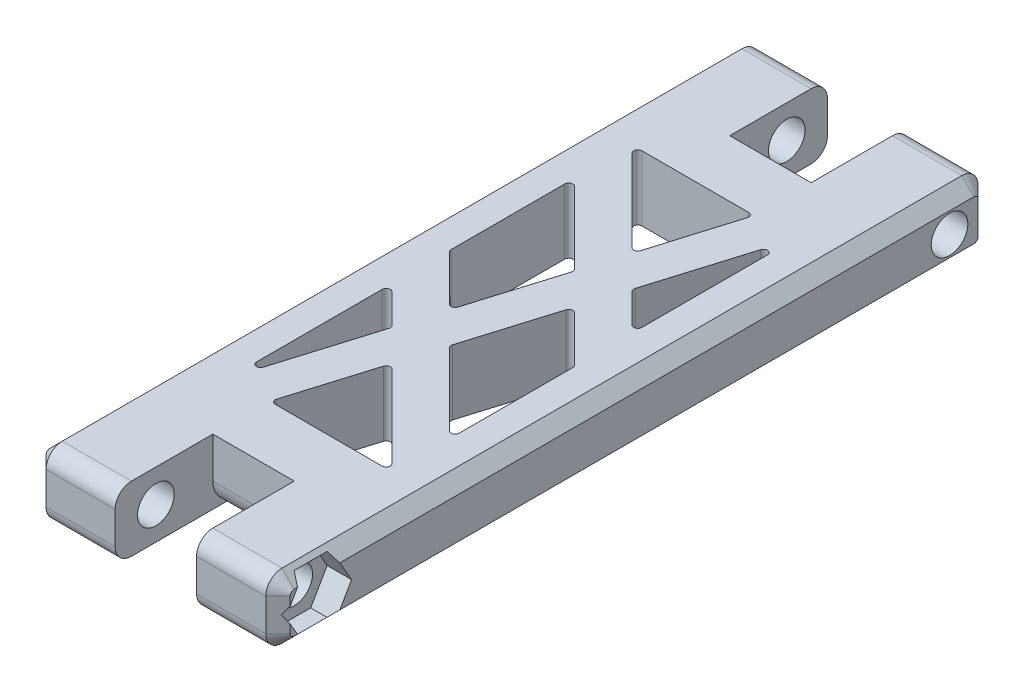
SolidWorks part; units mm, degrees
ref_plane "Front Plane" through (0, 0, 0) normal (0, 0, 1) x (1, 0, 0)
ref_plane "Top Plane" through (0, 0, 0) normal (0, 1, 0) x (1, 0, 0)
ref_plane "Right Plane" through (0, 0, 0) normal (1, 0, 0) x (0, 0, -1)
sketch "Sketch1" plane through (0, 0, 0) normal (0, 1, 0) x (1, 0, 0)
  line L1 (-15, 43.75) -> (15, 43.75)
  line L2 (-15, 43.75) -> (-15, -43.75)
  line L3 (-15, -43.75) -> (15, -43.75)
  line L4 (15, 43.75) -> (15, -43.75)
  line L5 (-15, 43.75) -> (15, -43.75) construction
  line L6 (-15, -43.75) -> (15, 43.75) construction
  point P0 (0, 0)
  dimension "D1" = 30
  dimension "D2" = 87.5
extrude "Boss-Extrude1" add sketch "Sketch1" along normal blind 8
sketch "Sketch2" plane through (0, 8, 0) normal (0, 1, 0) x (1, 0, 0)
  line L0 (15, 43.75) -> (-15, 43.75) construction
  line L1 (-5, 43.75) -> (5, 43.75)
  line L2 (-5, 43.75) -> (-5, 31.75)
  line L3 (-5, 31.75) -> (5, 31.75)
  line L4 (5, 43.75) -> (5, 31.75)
  line L5 (-15, -43.75) -> (15, -43.75) construction
  line L6 (5, -43.75) -> (-5, -43.75)
  line L7 (5, -43.75) -> (5, -31.75)
  line L8 (5, -31.75) -> (-5, -31.75)
  line L9 (-5, -43.75) -> (-5, -31.75)
  line L10 (15, -43.75) -> (15, 43.75) construction
  dimension "D1" = 10
  dimension "D2" = 10
  dimension "D3" = 10
  dimension "D4" = 12
  dimension "D5" = 12
  dimension "D6" = 10
extrude "Cut-Extrude1" cut sketch "Sketch2" against normal blind 8
sketch "Sketch3" plane through (15, 0, 0) normal (1, 0, 0) x (0, 0, -1)
  line L0 (-43.75, 8) -> (-43.75, 0) construction
  line L1 (-43.75, 8) -> (43.75, 8) construction
  circle A0 centre (-38.75, 4) radius 2.25
  dimension "D1" = 4.5
  dimension "D2" = 5
  dimension "D3" = 4
extrude "Cut-Extrude2" cut sketch "Sketch3" against normal through all
mirror "Mirror1" about plane through (0, 0, 0) normal (0, 0, 1) of "Cut-Extrude2"
fillet "Fillet1" radius 2 8 edges at (10, 0, -43.75) (10, 8, -43.75) (-10, 8, -43.75) (-10, 0, -43.75) (-10, 8, 43.75) (-10, 0, 43.75) (10, 0, 43.75) (10, 8, 43.75)
sketch "Sketch4" plane through (0, 8, 0) normal (0, 1, 0) x (1, 0, 0)
  line L0 (5, 24.75) -> (-10, 24.75)
  line L1 (-10, 24.75) -> (1.5116, 13.2384)
  line L2 (10, 4.75) -> (10, 24.75)
  line L3 (-10, -4.75) -> (-10, -24.75)
  line L4 (-5, -24.75) -> (10, -24.75)
  line L5 (10, -24.75) -> (-1.5116, -13.2384)
  line L6 (15, -41.75) -> (15, 41.75) construction
  line L7 (-15, 41.75) -> (-15, -41.75) construction
  line L8 (-10, 17.6789) -> (-10, 2.3211)
  line L9 (-10, 2.3211) -> (-3.7044, -3.9745)
  line L10 (10.0323, -17.7112) -> (10.0323, -2.3534)
  line L11 (10.0323, -2.3534) -> (3.7044, 3.9745)
  line L12 (-5, 31.75) -> (5, 31.75) construction
  line L13 (5, -31.75) -> (-5, -31.75) construction
  line L14 (5, 24.75) -> (1.5116, 13.2384)
  line L15 (-5, -24.75) -> (-1.5116, -13.2384)
  line L16 (0.1328, -7.8117) -> (3.7044, 3.9745)
  line L18 (5.3488, 9.4012) -> (10, 4.75)
  line L19 (-0.1328, 7.8117) -> (-10, 17.6789)
  line L20 (0.1328, -7.8117) -> (10.0323, -17.7112)
  line L21 (-5.3488, -9.4012) -> (-10, -4.75)
  line L22 (-5.3488, -9.4012) -> (-10, -24.75)
  line L23 (-0.1328, 7.8117) -> (-3.7044, -3.9745)
  line L24 (5.3488, 9.4012) -> (10, 24.75)
  dimension "D1" = 5
  dimension "D2" = 5
  dimension "D3" = 5
  dimension "D4" = 45
  dimension "D5" = 45
  dimension "D6" = 5
  dimension "D7" = 5
  dimension "D8" = 7
  dimension "D9" = 7
  dimension "D10" = 20
  dimension "D11" = 20
  dimension "D12" = 15
  dimension "D13" = 14
extrude "Cut-Extrude3" cut sketch "Sketch4" against normal through all
fillet "Fillet2" radius 3 2 edges at (0, 0, -31.75) (0, 0, 31.75)
chamfer "Chamfer1" distance 1.5 angle 45 16 edges at (15, 8, 0) (15, 7.4142, 43.1642) (15, 7.4142, -43.1642) (15, 4, 43.75) (15, 4, -43.75) (15, 0.5858, 43.1642) (15, 0.5858, -43.1642) (15, 0, 0) (-15, 0, 0) (-15, 0.5858, -43.1642) (-15, 0.5858, 43.1642) (-15, 4, -43.75) (-15, 4, 43.75) (-15, 7.4142, -43.1642) (-15, 7.4142, 43.1642) (-15, 8, 0)
fillet "Fillet3" radius 0.5 20 edges at (10, 4, -4.75) (10, 4, -24.75) (5.3488, 4, -9.4012) (3.7044, 4, -3.9745) (10.0323, 4, 2.3534) (10.0323, 4, 17.7112) (10, 4, 24.75) (-1.5116, 4, 13.2384) (-5, 4, 24.75) (0.1328, 4, 7.8117) (5, 4, -24.75) (-10, 4, -24.75) (1.5116, 4, -13.2384) (-0.1328, 4, -7.8117) (-3.7044, 4, 3.9745) (-10, 4, -17.6789) (-10, 4, -2.3211) (-5.3488, 4, 9.4012) (-10, 4, 24.75) (-10, 4, 4.75)
sketch "Sketch5" plane through (15, 0, 0) normal (1, 0, 0) x (0, 0, -1)
  line L1 (-34.7085, 4) -> (-36.7293, 7.5)
  line L2 (-36.7293, 7.5) -> (-40.7707, 7.5)
  line L3 (-40.7707, 7.5) -> (-42.7915, 4)
  line L4 (-42.7915, 4) -> (-40.7707, 0.5)
  line L5 (-40.7707, 0.5) -> (-36.7293, 0.5)
  line L6 (-36.7293, 0.5) -> (-34.7085, 4)
  circle A0 centre (-38.75, 4) radius 3.5 construction
  dimension "D1" = 7
extrude "Cut-Extrude4" cut sketch "Sketch5" against normal blind 3
